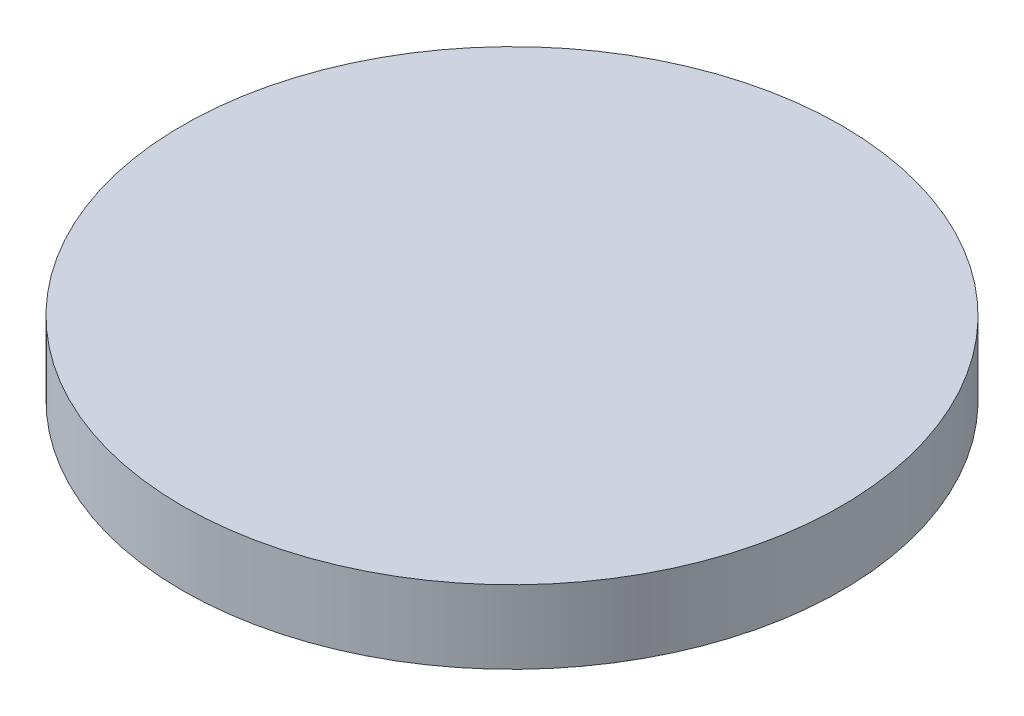
SolidWorks part; units mm, degrees
ref_plane "Front Plane" through (0, 0, 0) normal (0, 0, 1) x (1, 0, 0)
ref_plane "Top Plane" through (0, 0, 0) normal (0, 1, 0) x (1, 0, 0)
ref_plane "Right Plane" through (0, 0, 0) normal (1, 0, 0) x (0, 0, -1)
sketch "Sketch1" plane through (0, 0, 0) normal (0, 1, 0) x (1, 0, 0)
  circle A0 centre (0, 0) radius 10.35
  dimension "D1" = 20.7
extrude "Boss-Extrude1" add sketch "Sketch1" along normal blind 2.3
